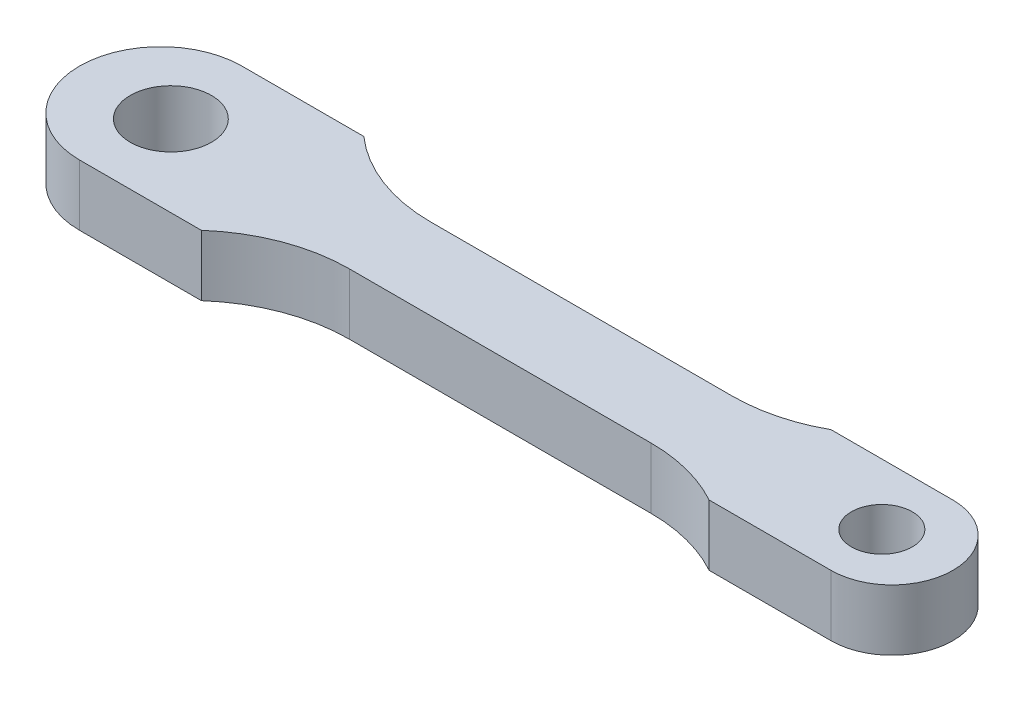
SolidWorks part; units mm, degrees
ref_plane "Front Plane" through (0, 0, 0) normal (0, 0, 1) x (1, 0, 0)
ref_plane "Top Plane" through (0, 0, 0) normal (0, 1, 0) x (1, 0, 0)
ref_plane "Right Plane" through (0, 0, 0) normal (1, 0, 0) x (0, 0, -1)
sketch "Sketch1" plane through (0, 0, 0) normal (0, 1, 0) x (1, 0, 0)
  line L0 (-17.5, 0) -> (17.5, 0) construction
  line L1 (-12, 2) -> (-12, 4)
  line L2 (-12, 2) -> (12, 2)
  line L3 (-12, 2) -> (-12, -2) construction
  line L4 (-12, -2) -> (12, -2)
  line L5 (12, 2) -> (12, -2) construction
  line L6 (-12, 2) -> (12, -2) construction
  line L7 (-12, -2) -> (12, 2) construction
  line L8 (-12, 4) -> (-18, 4)
  line L9 (-12, -2) -> (-12, -4)
  line L10 (-12, -4) -> (-18, -4)
  line L11 (12, 2) -> (12, 3)
  line L12 (12, 3) -> (18, 3)
  line L13 (12, -2) -> (12, -3)
  line L14 (12, -3) -> (18, -3)
  arc A0 (18, 3) -> (18, -3) centre (18, 0) cw
  circle A1 centre (17.5, 0) radius 1.5
  arc A2 (-18, 4) -> (-18, -4) centre (-18, 0) ccw
  circle A3 centre (-17.5, 0) radius 2
  arc A4 (-12, 4) -> (-6.7085, 2) centre (-6.7085, 10) ccw
  arc A5 (-12, -4) -> (-6.7085, -2) centre (-6.7085, -10) cw
  arc A6 (8.127, -2) -> (12, -3) centre (8.127, -10) cw
  arc A7 (8.127, 2) -> (12, 3) centre (8.127, 10) ccw
  point P0 (0, 0)
  point P4 (0, 0)
  point P29 (0, 0)
  point P30 (0, 0)
  dimension "D5" = 3
  dimension "D9" = 4
  dimension "D10" = 8
  dimension "D11" = 8
  dimension "D12" = 8
  dimension "D13" = 8
  dimension "D1" = 35
  dimension "D2" = 4
  dimension "D3" = 24
  dimension "D4" = 6
  dimension "D6" = 8
  dimension "D7" = 6
  dimension "D8" = 6
extrude "Boss-Extrude1" add sketch "Sketch1" along normal mid plane 3 contours L8 A2 L10 L9 L4 L13 L14 A0 L12 L11 L2 L1 A3 A1 | L4 A6 L13 | L9 A5 L4 | A4 L1 L2
sketch "Sketch2" plane through (0, 0, 0) normal (0, 1, 0) x (1, 0, 0)
  line L0 (-6.7085, 2) -> (12, 2) construction
  line L1 (8.127, 2) -> (12, 2)
  line L2 (12, 2) -> (12, 3)
  arc A0 (8.127, 2) -> (12, 3) centre (8.127, 10) ccw
  dimension "D1" = 8
extrude "Boss-Extrude2" add sketch "Sketch2" along normal mid plane 3
